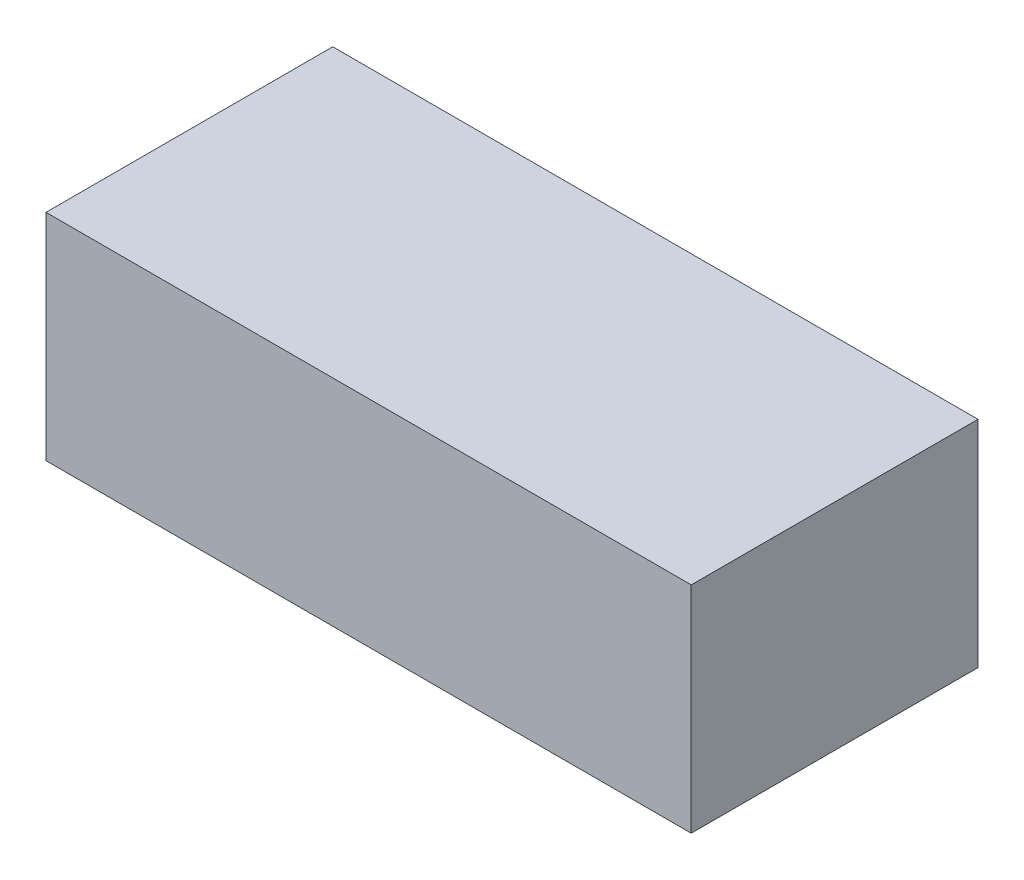
SolidWorks part; units mm, degrees
ref_plane "前视基准面" through (0, 0, 0) normal (0, 0, 1) x (1, 0, 0)
ref_plane "上视基准面" through (0, 0, 0) normal (0, 1, 0) x (1, 0, 0)
ref_plane "右视基准面" through (0, 0, 0) normal (1, 0, 0) x (0, 0, -1)
sketch "草图1" plane through (0, 0, 0) normal (0, 1, 0) x (1, 0, 0)
  line L1 (-9, 4) -> (9, 4)
  line L2 (-9, 4) -> (-9, -4)
  line L3 (-9, -4) -> (9, -4)
  line L4 (9, 4) -> (9, -4)
  line L5 (0, -4) -> (0, 4) construction
  line L6 (-9, 0) -> (9, 0) construction
  point P0 (0, 0)
  dimension "D1" = 18
  dimension "D2" = 8
extrude "凸台-拉伸1" add sketch "草图1" along normal blind 6 contours L3 L4 L1 L2
